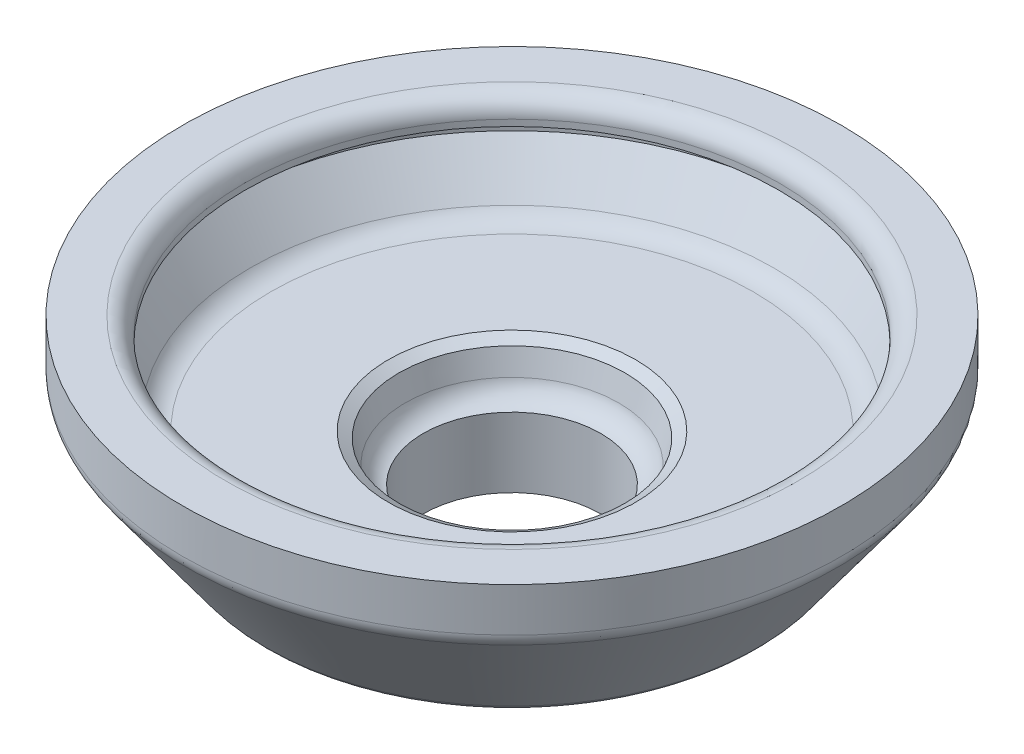
SolidWorks part; units mm, degrees
ref_plane "Front Plane" through (0, 0, 0) normal (0, 0, 1) x (1, 0, 0)
ref_plane "Top Plane" through (0, 0, 0) normal (0, 1, 0) x (1, 0, 0)
ref_plane "Right Plane" through (0, 0, 0) normal (1, 0, 0) x (0, 0, -1)
sketch "Sketch1" plane through (0, 0, 0) normal (0, 0, 1) x (1, 0, 0)
  line L1 (-4.5256, 11.1521) -> (-4.218, 10.0041)
  line L4 (-4.5025, 8.3218) -> (-9.5025, 8.3218)
  line L5 (-9.5025, 8.3218) -> (-13, 13.1239)
  line L6 (-13, 13.1239) -> (-13, 15.0951)
  line L7 (-13, 15.0951) -> (-10.55, 15.0951)
  line L8 (-10.55, 15.0951) -> (-10.55, 14.0951)
  line L9 (-10.55, 14.0951) -> (-11.55, 14.0951)
  line L10 (-11.55, 14.0951) -> (-11.55, 13.2451)
  line L11 (-11.55, 13.2451) -> (-10.0256, 11.1521)
  line L12 (-10.0256, 11.1521) -> (-4.5256, 11.1521)
  line L13 (-0.0025, 0) -> (-0.0025, 8.75) construction
  line L15 (-4.5025, 8.3218) -> (-4.5025, 6.5718)
  line L16 (-4.5025, 6.5718) -> (-3.5025, 6.5718)
  line L18 (-3.5025, 9.3218) -> (-3.5025, 6.5718)
  arc A1 (-4.218, 10.0041) -> (-3.5025, 9.3218) centre (-3.3003, 10.25) ccw
  dimension "D1" = 2.45
  dimension "D2" = 9.5
  dimension "D3" = 1
  dimension "D4" = 0.85
  dimension "D5" = 5.5
  dimension "D6" = 1
  dimension "D7" = 2.75
  dimension "D8" = 1
  dimension "D9" = 4.5
  dimension "D10" = 12.9975
revolve "Revolve1" add sketch "Sketch1" angle 360 about L13
fillet "Fillet1" radius 0.75 3 edges at (-0.0025, 8.3218, -4.5) (-0.0025, 8.3218, -9.5) (-0.0025, 13.1239, -12.9975)
fillet "Fillet2" radius 0.75 1 edges at (-0.0025, 15.0951, -10.5475)
fillet "Fillet3" radius 1 1 edges at (-0.0025, 11.1521, -10.0231)
chamfer "Chamfer1" distance 0.25 angle 45 1 edges at (-0.0025, 11.1521, -4.5231)
fillet "Fillet4" radius 0.21 1 edges at (-0.0025, 6.5718, -4.5)
